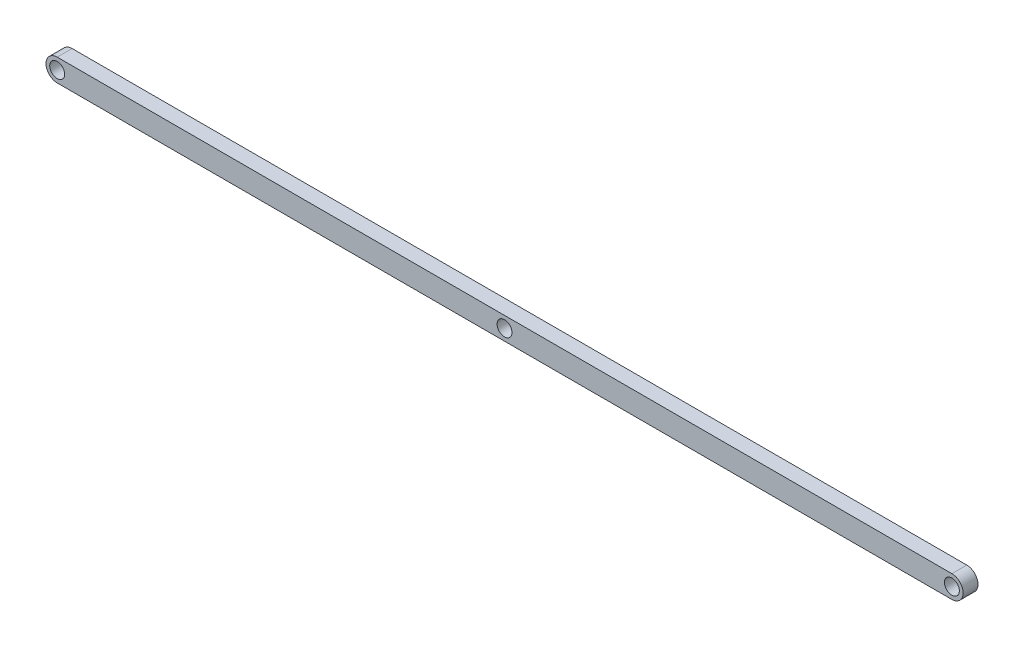
SolidWorks part; units mm, degrees
ref_plane "Front Plane" through (0, 0, 0) normal (0, 0, 1) x (1, 0, 0)
ref_plane "Top Plane" through (0, 0, 0) normal (0, 1, 0) x (1, 0, 0)
ref_plane "Right Plane" through (0, 0, 0) normal (1, 0, 0) x (0, 0, -1)
sketch "Sketch2" plane through (0, 0, 0) normal (0, 0, 1) x (1, 0, 0)
  line L0 (-76.2, 1.905) -> (0, 1.905)
  line L1 (76.2, -1.905) -> (-76.2, -1.905)
  line L2 (76.2, 1.905) -> (0, 1.905)
  circle A0 centre (0, 0) radius 1.27
  circle A1 centre (0, 0) radius 1.905
  circle A2 centre (-76.2, 0) radius 1.905
  circle A3 centre (-76.2, 0) radius 1.27
  circle A4 centre (76.2, 0) radius 1.905
  circle A5 centre (76.2, 0) radius 1.27
  point P7 (0, 1.905)
  point P14 (0, -1.905)
  dimension "D1" = 2.54
  dimension "D2" = 3.81
  dimension "D3" = 76.2
extrude "Boss-Extrude1" add sketch "Sketch2" along normal blind 2.54 contours A2 L1 A1 L0 | A2 A3 | A4 L2 A1 L1 | A4 A5 | A1 A0
